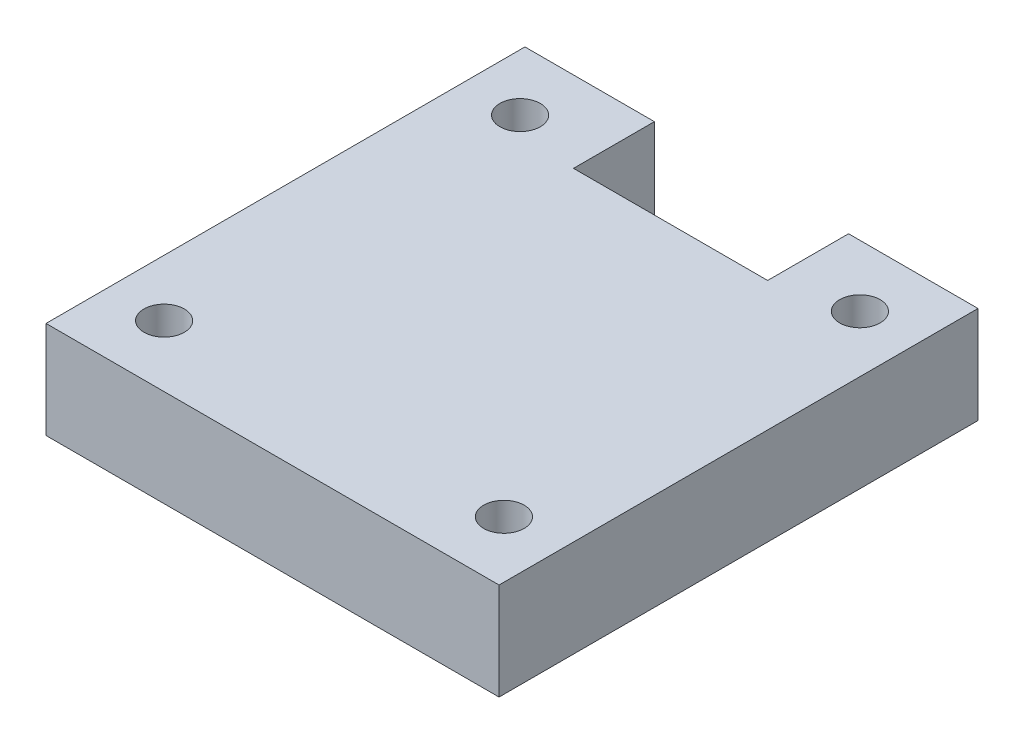
SolidWorks part; units mm, degrees
ref_plane "前视基准面" through (0, 0, 0) normal (0, 0, 1) x (1, 0, 0)
ref_plane "上视基准面" through (0, 0, 0) normal (0, 1, 0) x (1, 0, 0)
ref_plane "右视基准面" through (0, 0, 0) normal (1, 0, 0) x (0, 0, -1)
other "Configuration Table"
ref_plane "基准面1" through (0, 6, 0) normal (0, 1, 0) x (1, 0, 0)
sketch "草图2" plane through (0, 6, 0) normal (0, 1, 0) x (1, 0, 0)
  line L0 (37, 30) -> (-8, 30) construction
  line L1 (0.5, 29.8) -> (28.5, 29.8)
  line L2 (0.5, 29.8) -> (0.5, 0.2)
  line L3 (0.5, 0.2) -> (28.5, 0.2)
  line L4 (28.5, 29.8) -> (28.5, 0.2)
  line L7 (14.5, 32) -> (14.5, -2) construction
  line L8 (41, 32) -> (-12, 32) construction
  line L9 (-12, -2) -> (41, -2) construction
  line L10 (-8, 0) -> (37, 0) construction
  circle A0 centre (4, 26) radius 1.25
  circle A1 centre (25, 26) radius 1.25
  circle A2 centre (4, 4) radius 1.25
  circle A3 centre (25, 4) radius 1.25
  dimension "D2" = 2.5
  dimension "D3" = 2.5
  dimension "D4" = 2.5
  dimension "D5" = 2.5
  dimension "D1" = 28
  dimension "D6" = 0.2
  dimension "D7" = 0.2
extrude "凸台-拉伸1" add sketch "草图2" along normal up to surface (6 mm away)
sketch "草图3" plane through (0, 12, 0) normal (0, 1, 0) x (1, 0, 0)
  line L0 (14.5, 29.8) -> (14.5, 0.2) construction
  line L1 (28.5, 29.8) -> (0.5, 29.8) construction
  line L2 (0.5, 0.2) -> (28.5, 0.2) construction
  line L4 (8.5, 29.8) -> (20.5, 29.8)
  line L5 (8.5, 29.8) -> (8.5, 24.8)
  line L6 (8.5, 24.8) -> (20.5, 24.8)
  line L7 (20.5, 29.8) -> (20.5, 24.8)
  dimension "D1" = 12
  dimension "D2" = 5
extrude "切除-拉伸2" cut sketch "草图3" against normal through all
